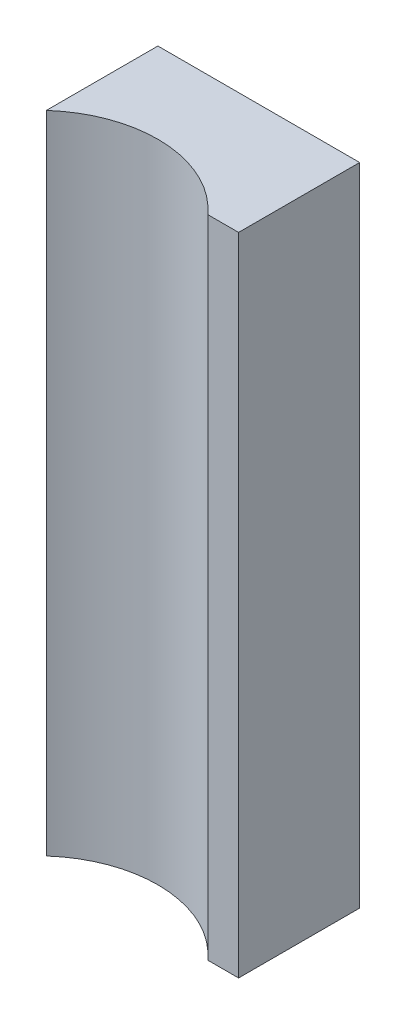
SolidWorks part; units mm, degrees
ref_plane "Front" through (0, 0, 0) normal (0, 0, 1) x (1, 0, 0)
ref_plane "Top" through (0, 0, 0) normal (0, 1, 0) x (1, 0, 0)
ref_plane "Right" through (0, 0, 0) normal (1, 0, 0) x (0, 0, -1)
sketch "Sketch2" plane through (0, 0, 0) normal (0, 1, 0) x (1, 0, 0)
  line L0 (19.05, 12.7) -> (19.05, 31.75)
  line L1 (19.05, 31.75) -> (-12.7, 31.75)
  line L2 (-12.7, 31.75) -> (-12.7, 14.199)
  line L3 (14.199, 12.7) -> (19.05, 12.7)
  arc A0 (14.199, 12.7) -> (-12.7, 14.199) centre (0, 0) ccw
  point P9 (16.6245, 12.7)
  dimension "D1" = 38.1
  dimension "D2" = 31.75
  dimension "D3" = 19.05
extrude "Boss-Extrude1" add sketch "Sketch2" along normal blind 101.6
